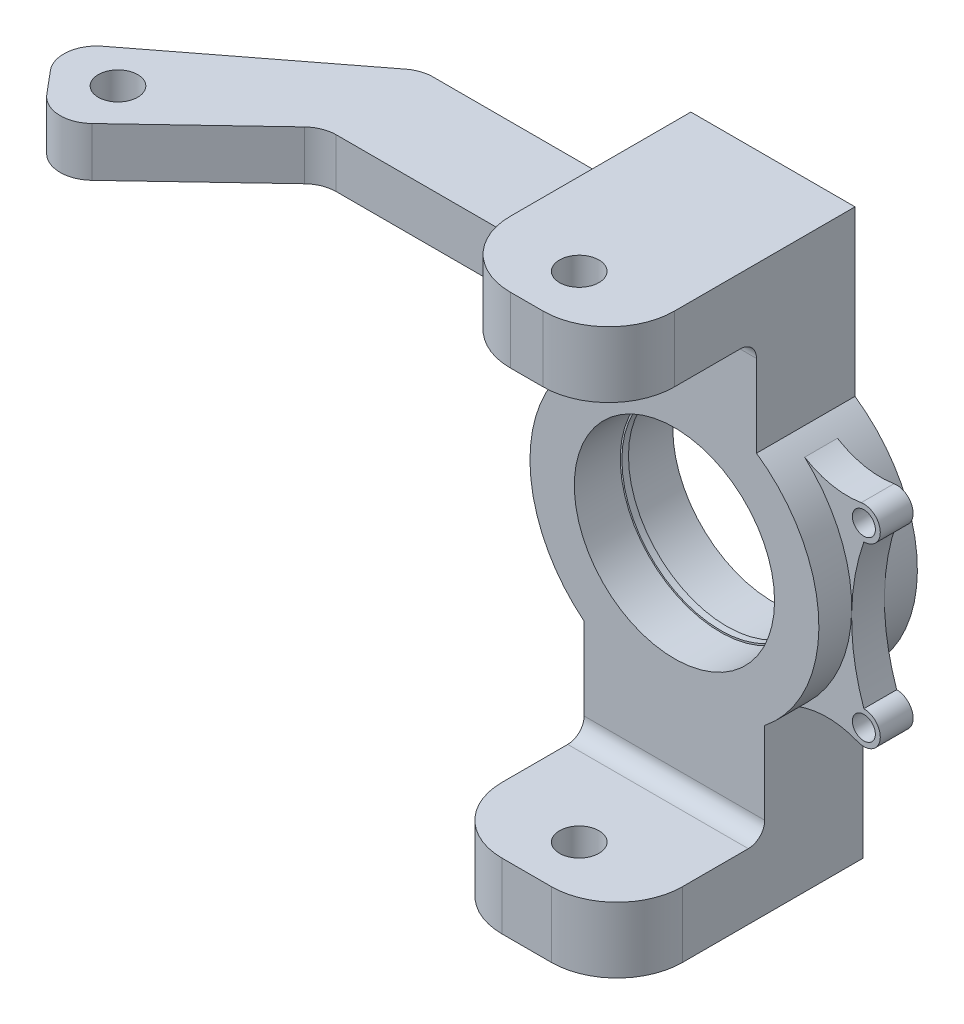
SolidWorks part; units mm, degrees
ref_plane "Front Plane" through (0, 0, 0) normal (0, 0, 1) x (1, 0, 0)
ref_plane "Top Plane" through (0, 0, 0) normal (0, 1, 0) x (1, 0, 0)
ref_plane "Right Plane" through (0, 0, 0) normal (1, 0, 0) x (0, 0, -1)
sketch "Sketch1" plane through (0, 0, 0) normal (0, 0, 1) x (1, 0, 0)
  line L0 (-25, 44) -> (25, 44)
  line L1 (-27.5, -44) -> (27.5, -44)
  line L2 (-27.5, -44) -> (-27.5, -34.3475) construction
  line L3 (27.5, -44) -> (27.5, -34.3475) construction
  line L4 (-25, 44) -> (-25, 36.2077) construction
  line L5 (25, 44) -> (25, 36.2077) construction
  line L6 (-25, 36.2077) -> (-25, 86.2077)
  line L7 (-25, 86.2077) -> (25, 86.2077)
  line L8 (25, 86.2077) -> (25, 36.2077)
  line L9 (-27.5, -34.3475) -> (-27.5, -84.3475)
  line L10 (-27.5, -84.3475) -> (27.5, -84.3475)
  line L11 (27.5, -84.3475) -> (27.5, -34.3475)
  circle A0 centre (0, 0) radius 31
  circle A1 centre (0, 0) radius 44
  point P7 (0, 44)
  point P10 (0, -44)
  dimension "D1" = 62
  dimension "D2" = 88
  dimension "D3" = 50
  dimension "D4" = 55
  dimension "D5" = 50
  dimension "D6" = 50
extrude "Boss-Extrude1" add sketch "Sketch1" along normal blind 30 contours A1 A0 | L8 L7 L6 L0 | A1 L8 L0 | A1 L0 L6 | A1 L9 L1 | A1 L1 L11 | L10 L11 L1 L9
sketch "Sketch3" plane through (-27.5, 0, 0) normal (-1, 0, 0) x (0, 0, 1)
  line L0 (30, -84.3475) -> (55, -84.3475)
  line L1 (75, -79.3475) -> (75, -69.3475)
  line L2 (55, -64.3475) -> (35, -64.3475)
  line L3 (30, -34.3475) -> (30, -84.3475) construction
  line L4 (30, -59.3475) -> (30, -34.3475)
  line L5 (55, -64.3475) -> (75, -64.3475)
  line L6 (75, -64.3475) -> (75, -69.3475)
  line L7 (75, -84.3475) -> (55, -84.3475)
  line L8 (75, -84.3475) -> (75, -79.3475)
  line L9 (0, -34.3475) -> (0, -84.3475)
  line L10 (0, -84.3475) -> (30, -84.3475)
  line L11 (30, -84.3475) -> (30, -34.3475)
  line L12 (30, -34.3475) -> (0, -34.3475)
  line L15 (30, -84.3475) -> (30, -34.3475)
  arc A2 (35, -64.3475) -> (30, -59.3475) centre (35, -59.3475) cw
  point P17 (30, -64.3475)
  dimension "D1" = 45
  dimension "D4" = 0
extrude "Boss-Extrude2" add sketch "Sketch3" against normal blind 55
sketch "Sketch5" plane through (-25, 0, 0) normal (-1, 0, 0) x (0, 0, 1)
  line L0 (30, 86.2077) -> (55, 86.2077)
  line L1 (75, 81.2077) -> (75, 71.2077)
  line L2 (70, 66.2077) -> (35, 66.2077)
  line L3 (30, 36.2077) -> (30, 86.2077) construction
  line L4 (30, 61.2077) -> (30, 36.2077)
  line L5 (55, 86.2077) -> (75, 86.2077)
  line L6 (75, 86.2077) -> (75, 81.2077)
  line L7 (75, 66.2077) -> (70, 66.2077)
  line L8 (75, 66.2077) -> (75, 71.2077)
  line L9 (0, 86.2077) -> (0, 36.2077)
  line L10 (0, 36.2077) -> (30, 36.2077)
  line L11 (30, 36.2077) -> (30, 86.2077)
  line L12 (30, 86.2077) -> (0, 86.2077)
  line L13 (0, 86.2077) -> (0, 36.2077)
  line L14 (0, 36.2077) -> (30, 36.2077)
  line L16 (30, 86.2077) -> (0, 86.2077)
  arc A2 (30, 61.2077) -> (35, 66.2077) centre (35, 61.2077) cw
  point P11 (75, 86.2077)
  point P14 (75, 66.2077)
  point P17 (30, 66.2077)
  dimension "D2" = 20
  dimension "D4" = 0
extrude "Boss-Extrude3" add sketch "Sketch5" against normal blind 50
sketch "Sketch7" plane through (0, -64.3475, 0) normal (0, 1, 0) x (1, 0, 0)
  line L0 (-27.5, -35) -> (-27.5, -55)
  line L1 (-7.5, -75) -> (7.5, -75)
  line L2 (27.5, -55) -> (27.5, -35)
  line L3 (0, -75) -> (0, -59)
  arc A0 (27.5, -55) -> (7.5, -75) centre (7.5, -55) cw
  arc A1 (-7.5, -75) -> (-27.5, -55) centre (-7.5, -55) cw
  circle A2 centre (0, -59) radius 6
  point P10 (27.5, -75)
  point P13 (-27.5, -75)
  line M2 (-27.5, -35) -> (-27.5, -75)
  line M3 (-27.5, -75) -> (27.5, -75)
  line M4 (27.5, -75) -> (27.5, -35)
  dimension "D1" = 20
  dimension "D2" = 16
extrude "Cut-Extrude4" cut sketch "Sketch7" against normal through all contours A1 M3 M2 | A0 M4 M3 | A2
sketch "Sketch9" plane through (0, 86.2077, 0) normal (0, 1, 0) x (1, 0, 0)
  line L0 (-25, 0) -> (-25, -55)
  line L1 (-5, -75) -> (5, -75)
  line L2 (25, -55) -> (25, 0)
  line L3 (0, -75) -> (0, -59)
  arc A0 (25, -55) -> (5, -75) centre (5, -55) cw
  arc A1 (-5, -75) -> (-25, -55) centre (-5, -55) cw
  circle A2 centre (0, -59) radius 6
  point P10 (25, -75)
  point P13 (-25, -75)
  dimension "D1" = 20
  dimension "D3" = 12
  dimension "D2" = 16
extrude "Cut-Extrude6" cut sketch "Sketch9" against normal blind 50
sketch3d "3DSketch1"
  line L0 (-25, 66.2077, 55) -> (-25, 81.2077, 55)
  line L1 (-25, 66.2077, 55) -> (-25, 86.2077, 55) construction
  line L2 (-25, 81.2077, 55) -> (-25, 81.2077, 25)
  line L3 (-25, 81.2077, 25) -> (-25, 66.2077, 25)
  line L4 (-25, 66.2077, 25) -> (-25, 66.2077, 55)
  dimension "D1" = 15
  dimension "D2" = 30
  dimension "D3" = 15
extrude "Boss-Extrude4" add sketch "3DSketch1" along direction (-1, 0, 0) on the side of the normal blind 57 contours L0 L2 L3 L4
sketch "Sketch11" plane through (0, 81.2077, 0) normal (0, 1, 0) x (1, 0, 0)
  line L0 (-82, -25) -> (-82, -55)
  line L2 (-82, -55) -> (-82, -25) construction
  line L3 (-82, -40) -> (-135.6231, -84.9951)
  line L4 (-138.4988, -81.5681) -> (-132.7474, -88.4222)
  line L5 (-136.9314, -67.2109) -> (-82, -25)
  line L6 (-118.2148, -89.2589) -> (-84.8917, -57.7355)
  line L7 (-78.0195, -55) -> (-25, -55)
  arc A0 (-118.2148, -89.2589) -> (-132.7474, -88.4222) centre (-125.087, -81.9943) cw
  arc A1 (-138.4988, -81.5681) -> (-136.9314, -67.2109) centre (-130.8383, -75.1402) cw
  arc A2 (-25, -55) -> (-5, -75) centre (-5, -55) ccw construction
  arc A3 (-78.0195, -55) -> (-84.8917, -57.7355) centre (-78.0195, -65) ccw
  point P10 (-135.6231, -84.9951)
  point P16 (-125.9251, -96.5527)
  point P19 (-145.2088, -73.5714)
  line M4 (-82, -25) -> (-82, -55)
  dimension "D3" = 10
  dimension "D4" = 10
  dimension "D1" = 30
  dimension "D2" = 70
  dimension "D5" = 50
extrude "Boss-Extrude5" add sketch "Sketch11" against normal blind 15 contours A0 L6 L0 L3 L4 | A1 L4 L3 L5 M4
sketch "Sketch13" plane through (0, 81.2077, 0) normal (0, 1, 0) x (1, 0, 0)
  line L0 (-136.9314, -67.2109) -> (-84.6947, -27.0707)
  line L1 (-78.6016, -25) -> (-25, -25)
  line L2 (-84.6947, -27.0707) -> (-82, -25)
  line L3 (-82, -25) -> (-78.6016, -25)
  arc A0 (-78.6016, -25) -> (-84.6947, -27.0707) centre (-78.6016, -35) ccw
  point P8 (-82, -25)
  line M1 (-25, -25) -> (-82, -25)
  line M2 (-82, -25) -> (-136.9314, -67.2109)
  dimension "D1" = 10
extrude "Cut-Extrude8" cut sketch "Sketch13" against normal blind 20 contours A0 M1 M2
sketch "Sketch14" plane through (0, 81.2077, 0) normal (0, 1, 0) x (1, 0, 0)
  line L0 (-135.6231, -84.9951) -> (-124.1324, -75.3533)
  line L1 (-138.4988, -81.5681) -> (-132.7474, -88.4222) construction
  line L2 (-135.6231, -84.9951) -> (-132.7474, -88.4222)
  circle A0 centre (-124.1324, -75.3533) radius 6
  dimension "D3" = 12
  dimension "D1" = 90
  dimension "D2" = 15
extrude "Cut-Extrude9" cut sketch "Sketch14" against normal blind 20
sketch "Sketch22" plane through (0, 0, 0) normal (0, 1, 0) x (1, 0, 0)
  line L1 (0, -9) -> (0, -16)
  point P0 (0, -12.5)
  dimension "D2" = 7
sketch3d "3DSketch5"
  point P14 (0, 0, 16)
sketch "Sketch29" plane through (0, 0, 30) normal (0, 0, 1) x (1, 0, 0)
  circle A0 centre (0, 0) radius 30.5
  circle A1 centre (0, 0) radius 30
  dimension "D1" = 61
  dimension "D2" = 60
extrude "Cut-Extrude10" cut sketch "Sketch29" against normal through all contours A1
sketch "Sketch31" plane through (0, 0, 30) normal (0, 0, 1) x (1, 0, 0)
  circle A0 centre (0, 0) radius 30.5
  dimension "D1" = 61
extrude "Cut-Extrude11" cut sketch "Sketch31" against normal blind 14 contours A0
sketch "Sketch32" plane through (0, 0, 0) normal (0, 0, -1) x (-1, 0, 0)
  circle A0 centre (0, 0) radius 30.5
  dimension "D1" = 61
extrude "Cut-Extrude12" cut sketch "Sketch32" against normal blind 14 contours A0
sketch "Sketch33" plane through (0, 0, 30) normal (0, 0, 1) x (1, 0, 0)
  arc A0 (27.5, -34.3475) -> (25, 36.2077) centre (0, 0) ccw
  circle A2 centre (47.7003, 24.1773) radius 5
  circle A3 centre (47.7003, 24.1773) radius 3.5
  circle A4 centre (47.7003, -29.8227) radius 5
  circle A5 centre (47.7003, -29.8227) radius 3.5
  arc A6 (46.8819, 29.1098) -> (25, 36.2077) centre (42.7897, 53.7726) cw
  arc A7 (45.8374, -34.4627) -> (27.5, -34.3475) centre (36.5225, -57.6626) ccw
  arc A8 (47.7003, 19.1773) -> (47.7003, -24.8227) centre (110.601, -2.8227) ccw
  arc A9 (25, 36.2077) -> (27.5, -34.3475) centre (0, 0) cw
  arc M9 (27.5, -34.3475) -> (25, 36.2077) centre (0, 0) ccw
  dimension "D4" = 10
  dimension "D5" = 7
  dimension "D8" = 7
  dimension "D9" = 10
  dimension "D1" = 25
  dimension "D2" = 25
  dimension "D7" = 54
extrude "Boss-Extrude6" add sketch "Sketch33" against normal blind 30 contours A8 A2 A6 A0 | A8 A7 A4 M9 | A2 A3 | A4 A5
sketch "Sketch34" plane through (0, 0, 30) normal (0, 0, 1) x (1, 0, 0)
  circle A0 centre (47.7003, 24.1773) radius 3.5
  circle A1 centre (47.7003, 24.1773) radius 5
  circle A2 centre (47.7003, -29.8227) radius 3.5
  circle A3 centre (47.7003, -29.8227) radius 5
  arc A4 (27.5, -34.3475) -> (29.6686, 32.4927) centre (0, 0) ccw
  arc A5 (29.6686, 32.4927) -> (46.8819, 29.1098) centre (42.7897, 53.7726) ccw
  arc A6 (47.7003, 19.1773) -> (47.7003, -24.8227) centre (110.601, -2.8227) ccw
  arc A7 (45.8374, -34.4627) -> (27.5, -34.3475) centre (36.5225, -57.6626) ccw
  arc M4 (27.5, -34.3475) -> (45.8374, -34.4627) centre (36.5225, -57.6626) cw
  arc M5 (45.8374, -34.4627) -> (47.7003, -24.8227) centre (47.7003, -29.8227) ccw
  arc M6 (47.7003, -24.8227) -> (47.7003, 19.1773) centre (110.601, -2.8227) cw
  arc M7 (47.7003, 19.1773) -> (46.8819, 29.1098) centre (47.7003, 24.1773) ccw
  arc M8 (46.8819, 29.1098) -> (29.6686, 32.4927) centre (42.7897, 53.7726) cw
  circle M16 centre (47.7003, 24.1773) radius 3.5
  circle M17 centre (47.7003, -29.8227) radius 3.5
extrude "Cut-Extrude13" cut sketch "Sketch34" against normal blind 10 contours A4 A1 M6 M8 | A1 M7 M16 | A4 A3 M4 M6 | A3 M5 M17
sketch "Sketch35" plane through (0, 0, 0) normal (0, 0, -1) x (-1, 0, 0)
  arc A0 (-29.6686, 32.4927) -> (-27.5, -34.3475) centre (0, 0) ccw
  circle A1 centre (-47.7003, 24.1773) radius 3.5
  circle A2 centre (-47.7003, 24.1773) radius 5
  circle A3 centre (-47.7003, -29.8227) radius 3.5
  circle A4 centre (-47.7003, -29.8227) radius 5
  arc A5 (-46.8819, 29.1098) -> (-29.6686, 32.4927) centre (-42.7897, 53.7726) ccw
  arc A6 (-47.7003, 19.1773) -> (-47.7003, -24.8227) centre (-110.601, -2.8227) cw
  arc A7 (-45.8374, -34.4627) -> (-27.5, -34.3475) centre (-36.5225, -57.6626) cw
  arc M7 (-29.6686, 32.4927) -> (-46.8819, 29.1098) centre (-42.7897, 53.7726) cw
  arc M8 (-46.8819, 29.1098) -> (-47.7003, 19.1773) centre (-47.7003, 24.1773) ccw
  arc M9 (-47.7003, 19.1773) -> (-47.7003, -24.8227) centre (-110.601, -2.8227) cw
  arc M10 (-47.7003, -24.8227) -> (-45.8374, -34.4627) centre (-47.7003, -29.8227) ccw
  arc M11 (-45.8374, -34.4627) -> (-27.5, -34.3475) centre (-36.5225, -57.6626) cw
  circle M15 centre (-47.7003, 24.1773) radius 3.5
  circle M16 centre (-47.7003, -29.8227) radius 3.5
extrude "Cut-Extrude14" cut sketch "Sketch35" against normal blind 10 contours A2 A0 M9 M7 | A2 M8 M15 | A4 A0 M11 M9 | A4 M10 M16
sketch "Sketch36" plane through (0, 86.2077, 0) normal (0, 1, 0) x (1, 0, 0)
  line L0 (0, -59) -> (-159.4606, -59)
  line L1 (0, -59) -> (-124.1324, -75.3533)
  circle A0 centre (0, -59) radius 6
